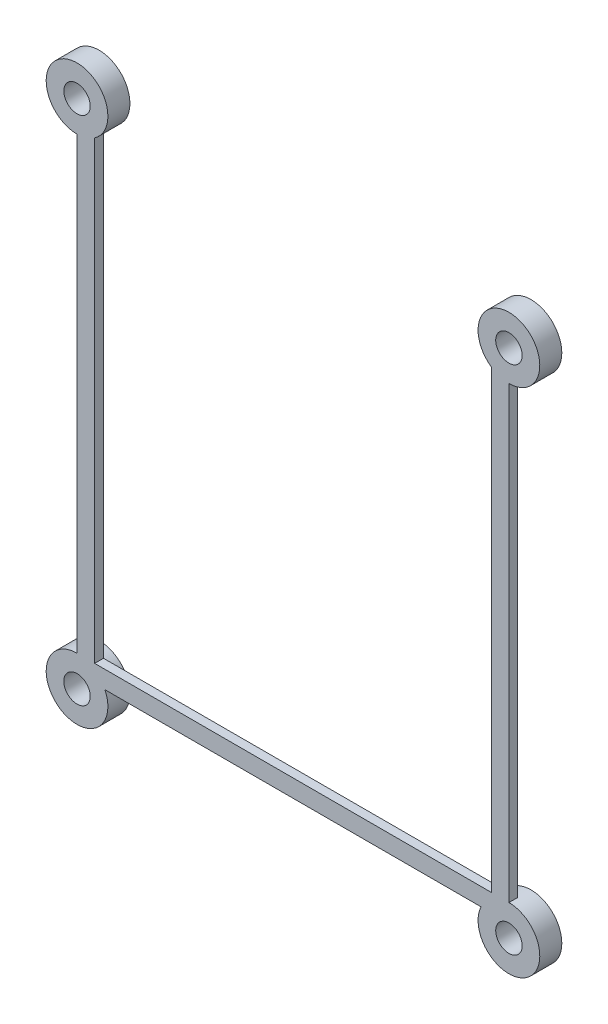
SolidWorks part; units mm, degrees
ref_plane "Plan de face" through (0, 0, 0) normal (0, 0, 1) x (1, 0, 0)
ref_plane "Plan de dessus" through (0, 0, 0) normal (0, 1, 0) x (1, 0, 0)
ref_plane "Plan de droite" through (0, 0, 0) normal (1, 0, 0) x (0, 0, -1)
sketch "Esquisse1" plane through (0, 0, 0) normal (0, 0, 1) x (1, 0, 0)
  line L0 (-24.5, 29) -> (24.5, 29) construction
  line L1 (24.5, 29) -> (24.5, -29) construction
  line L2 (24.5, -29) -> (-24.5, -29) construction
  line L3 (-24.5, -29) -> (-24.5, 29) construction
  circle A0 centre (-24.5, 29) radius 3.5
  circle A1 centre (24.5, 29) radius 3.5
  circle A2 centre (-24.5, -29) radius 3.5
  circle A3 centre (24.5, -29) radius 3.5
  circle A4 centre (-24.5, 29) radius 1.5
  circle A5 centre (24.5, 29) radius 1.5
  circle A6 centre (24.5, -29) radius 1.5
  circle A7 centre (-24.5, -29) radius 1.5
  point P12 (0, 29)
  point P13 (-24.5, 0)
  dimension "D1" = 3
  dimension "D2" = 7
  dimension "D3" = 49
  dimension "D4" = 58
extrude "Boss.-Extru.2" add sketch "Esquisse1" along normal blind 2.5
sketch "Esquisse3" plane through (0, 0, 2.5) normal (0, 0, 1) x (1, 0, 0)
  line L1 (24.5, 27.5) -> (24.5, -27.5)
  line L3 (-24.5, -27.5) -> (-24.5, 27.5)
  line L5 (22.5, 27.5) -> (22.5, -25.5)
  line L7 (-22.5, -25.5) -> (-22.5, 27.5)
  line L10 (-24.5, -27.5) -> (24.5, -27.5)
  line L11 (22.5, -25.5) -> (-22.5, -25.5)
  line L12 (-24.5, 27.5) -> (-22.5, 27.5)
  line L13 (22.5, 27.5) -> (24.5, 27.5)
  circle A0 centre (-24.5, 29) radius 1.5 construction
  circle A1 centre (24.5, 29) radius 1.5 construction
  circle A2 centre (24.5, -29) radius 1.5 construction
  circle A3 centre (-24.5, -29) radius 1.5 construction
  dimension "D2" = 2
  dimension "D3" = 2
  dimension "D4" = 2
extrude "Boss.-Extru.3" add sketch "Esquisse3" against normal blind 1
